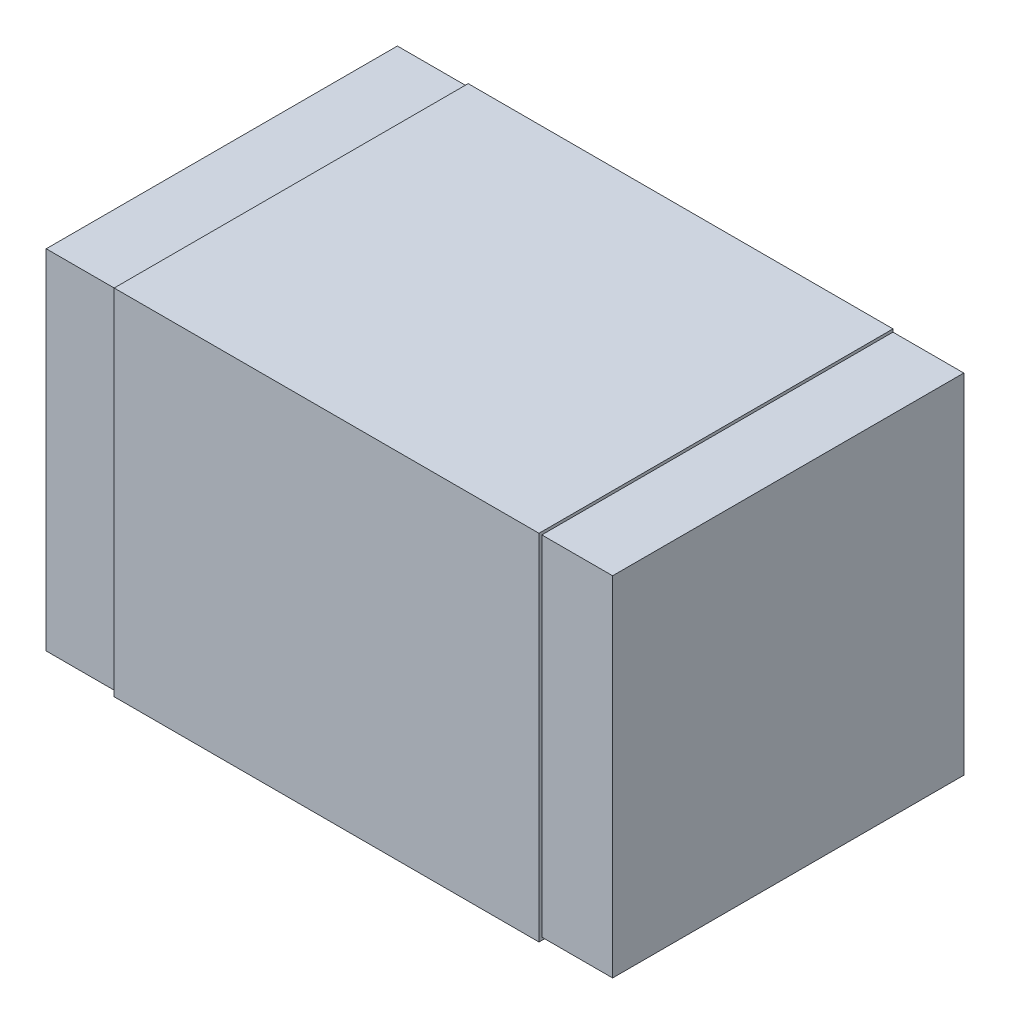
SolidWorks part; units mm, degrees
ref_plane "Front Plane" through (0, 0, 0) normal (0, 0, 1) x (1, 0, 0)
ref_plane "Top Plane" through (0, 0, 0) normal (0, 1, 0) x (1, 0, 0)
ref_plane "Right Plane" through (0, 0, 0) normal (1, 0, 0) x (0, 0, -1)
sketch "Sketch1" plane through (0, 0, 0) normal (0, 0, 1) x (1, 0, 0)
  line L1 (-0.75, 0.625) -> (0.75, 0.625)
  line L2 (-0.75, 0.625) -> (-0.75, -0.625)
  line L3 (-0.75, -0.625) -> (0.75, -0.625)
  line L4 (0.75, 0.625) -> (0.75, -0.625)
  line L5 (-0.75, 0.625) -> (0.75, -0.625) construction
  line L6 (-0.75, -0.625) -> (0.75, 0.625) construction
  point P0 (0, 0)
  dimension "D1" = 1.5
  dimension "D2" = 1.25
extrude "Boss-Extrude1" add sketch "Sketch1" along normal blind 1.25
sketch "Sketch4" plane through (0, 0, 0) normal (0, 0, -1) x (-1, 0, 0)
  line L0 (-0.75, -0.625) -> (-0.75, 0.625) construction
  line L1 (-0.75, 0.615) -> (-1, 0.615)
  line L2 (-0.75, 0.615) -> (-0.75, -0.615)
  line L3 (-0.75, -0.615) -> (-1, -0.615)
  line L4 (-1, 0.615) -> (-1, -0.615)
  line L5 (0.75, 0.625) -> (0.75, -0.625) construction
  line L6 (0.75, 0.615) -> (1, 0.615)
  line L7 (0.75, 0.615) -> (0.75, -0.615)
  line L8 (0.75, -0.615) -> (1, -0.615)
  line L9 (1, 0.615) -> (1, -0.615)
  line L10 (-0.75, 0.625) -> (0.75, 0.625) construction
  line L11 (0.75, -0.625) -> (-0.75, -0.625) construction
  dimension "D1" = 0.25
  dimension "D2" = 0.25
  dimension "D3" = 0.01
  dimension "D4" = 0.01
  dimension "D5" = 0.01
  dimension "D6" = 0.01
extrude "Boss-Extrude3" add sketch "Sketch4" against normal blind 1.24
